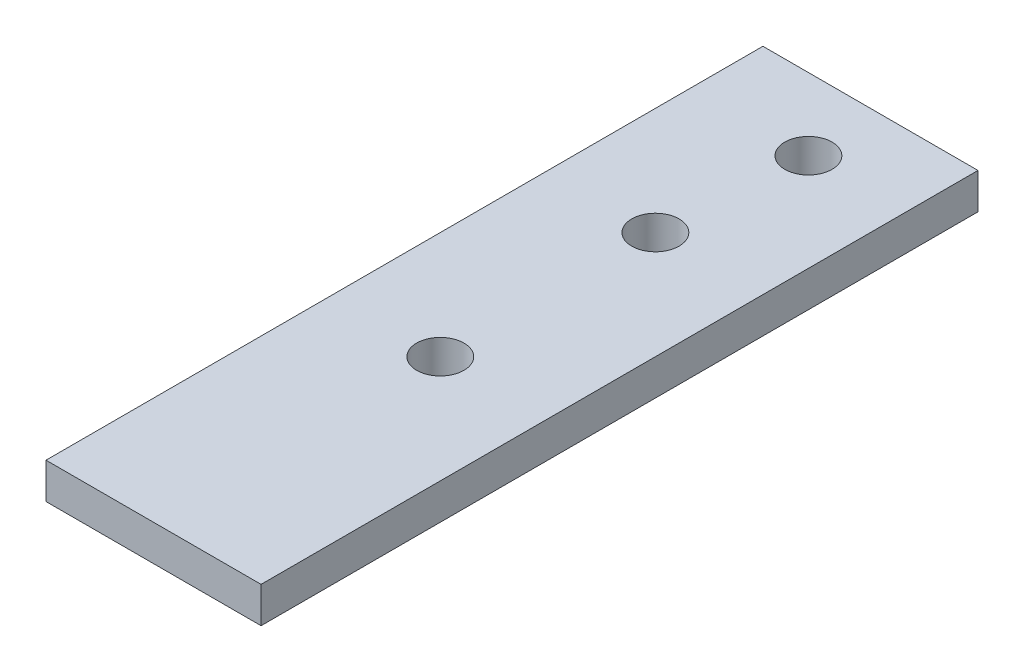
SolidWorks part; units mm, degrees
ref_plane "Front Plane" through (0, 0, 0) normal (0, 0, 1) x (1, 0, 0)
ref_plane "Top Plane" through (0, 0, 0) normal (0, 1, 0) x (1, 0, 0)
ref_plane "Right Plane" through (0, 0, 0) normal (1, 0, 0) x (0, 0, -1)
sketch "Sketch1" plane through (0, 0, 0) normal (0, 1, 0) x (1, 0, 0)
  line L0 (19.05, 50.8) -> (21.5594, 86.6859)
  line L1 (0, 0) -> (38.1, 0)
  line L2 (0, 0) -> (0, 88.9)
  line L3 (0, 88.9) -> (38.1, 88.9)
  line L4 (38.1, 0) -> (38.1, 88.9)
  line L5 (21.5594, 86.6859) -> (19.05, 86.6859)
  line L6 (19.05, 86.6859) -> (19.05, 50.8)
  circle A0 centre (19.05, 12.7) radius 4.191
  circle A1 centre (19.05, 50.8) radius 4.191
  circle A2 centre (20.8218, 76.1381) radius 4.191
  dimension "D3" = 8.382
  dimension "D1" = 88.9
  dimension "D2" = 38.1
  dimension "D4" = 38.1
  dimension "D5" = 12.7
  dimension "D6" = 4
  dimension "D7" = 0
  dimension "D8" = 25.4
  dimension "D9" = 19.05
extrude "Boss-Extrude1" add sketch "Sketch1" along normal blind 6.35 contours L2 L1 L4 L3 | A0 | A1 | A2
sketch "Sketch3" plane through (0, 0, 0) normal (0, 0, 1) x (1, 0, 0)
  line L1 (0, 6.35) -> (38.1, 6.35)
  line L2 (0, 6.35) -> (0, 0)
  line L3 (0, 0) -> (38.1, 0)
  line L4 (38.1, 6.35) -> (38.1, 0)
extrude "Boss-Extrude2" add sketch "Sketch3" along normal blind 38.1
